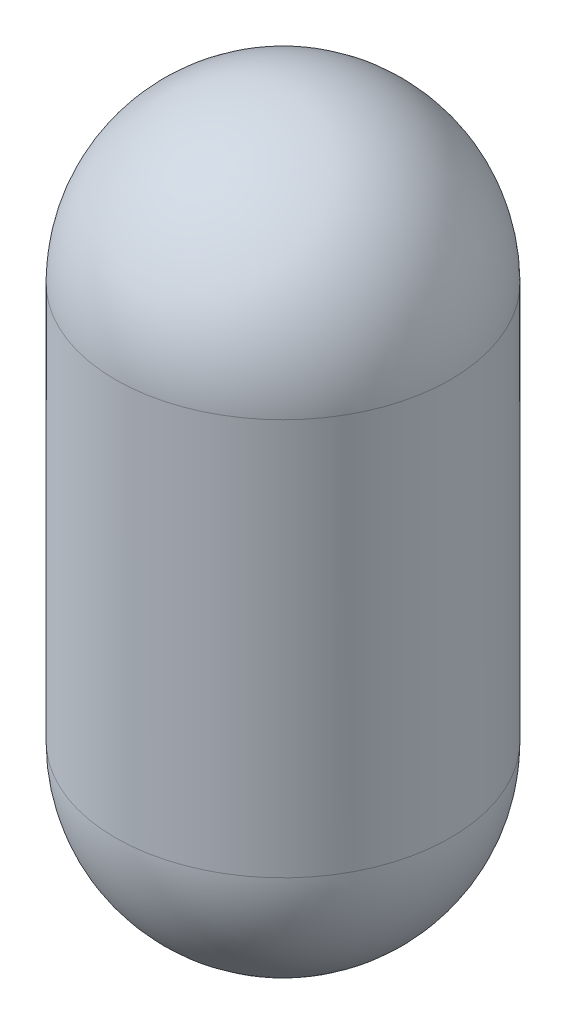
SolidWorks part; units mm, degrees
ref_plane "Front Plane" through (0, 0, 0) normal (0, 0, 1) x (1, 0, 0)
ref_plane "Top Plane" through (0, 0, 0) normal (0, 1, 0) x (1, 0, 0)
ref_plane "Right Plane" through (0, 0, 0) normal (1, 0, 0) x (0, 0, -1)
sketch "Sketch1" plane through (0, 0, 0) normal (0, 0, 1) x (1, 0, 0)
  line L0 (0, 87.9475) -> (0, -87.9475) construction
  line L2 (-74.295, 87.9475) -> (-74.295, -87.9475)
  line L3 (-71.12, 87.9475) -> (-71.12, -87.9475)
  line L5 (0, 162.2425) -> (0, 159.0675)
  line L6 (0, -162.2425) -> (0, -159.0675)
  line L7 (-74.295, -87.9475) -> (0, -87.9475) construction
  line L8 (74.2937, 88.3837) -> (74.295, -87.947) construction
  line L9 (71.1187, 88.3743) -> (71.12, -87.947) construction
  line L10 (-74.295, 87.9475) -> (0, 87.9475) construction
  line L11 (0, 159.0675) -> (0, 87.9475) construction
  line L12 (0, -159.0675) -> (0, -87.9475) construction
  arc A0 (0, 162.2425) -> (-74.295, 87.9475) centre (0, 87.9475) ccw
  arc A1 (-74.295, -87.9475) -> (0, -162.2425) centre (0, -87.9475) ccw
  arc A2 (0, 159.0675) -> (-71.12, 87.9475) centre (0, 87.9475) ccw
  arc A3 (-71.12, -87.9475) -> (0, -159.0675) centre (0, -87.9475) ccw
  arc A4 (-71.12, -87.9475) -> (71.12, -87.947) centre (0, -87.9475) ccw construction
  arc A5 (-74.295, -87.9475) -> (74.295, -87.947) centre (0, -87.9475) ccw construction
  arc A6 (74.2937, 88.3837) -> (-74.295, 87.9475) centre (0, 87.9475) ccw construction
  arc A7 (71.1187, 88.3743) -> (-71.12, 87.9475) centre (0, 87.9475) ccw construction
  dimension "D1" = 175.895
  dimension "D2" = 74.295
  dimension "D3" = 3.175
revolve "Revolve3" add sketch "Sketch1" angle 360 about L0
